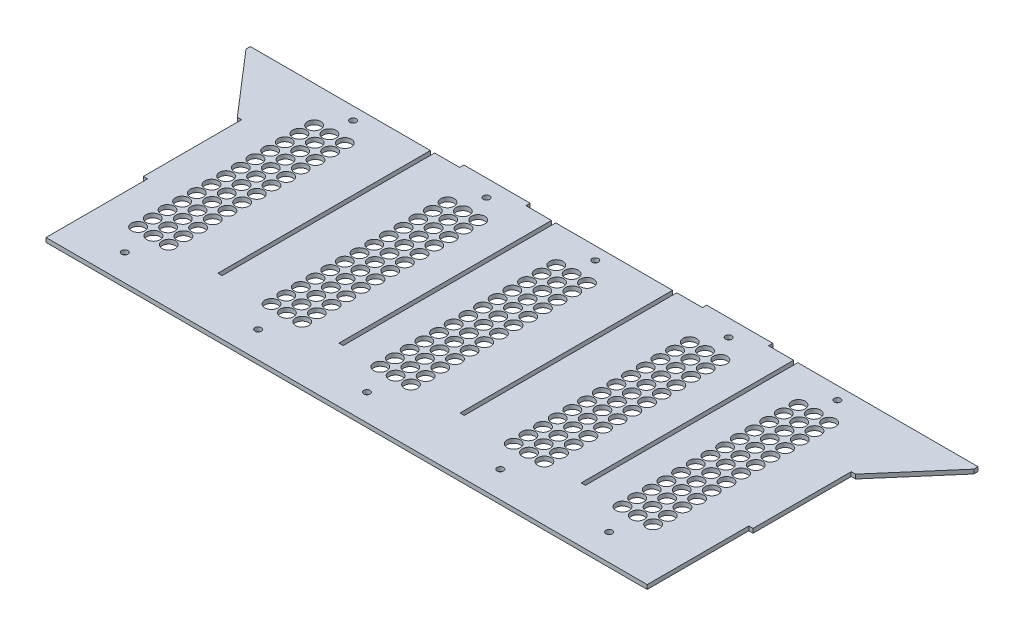
SolidWorks part; units mm, degrees
material "6061-T6 (SS)"
ref_plane "X-Y Datum" through (0, 0, 0) normal (0, 0, 1) x (1, 0, 0)
ref_plane "X-Z Datum" through (0, 0, 0) normal (0, 1, 0) x (1, 0, 0)
ref_plane "Y-Z Datum" through (0, 0, 0) normal (1, 0, 0) x (0, 0, -1)
sketch "Sketch1" plane through (0, 0, 0) normal (0, 0, 1) x (1, 0, 0)
  line L1 (-228.6115, -1.5875) -> (228.6115, -1.5875)
  line L2 (-228.6115, -1.5875) -> (-228.6115, 1.5875)
  line L3 (-228.6115, 1.5875) -> (228.6115, 1.5875)
  line L4 (228.6115, -1.5875) -> (228.6115, 1.5875)
  line L5 (-228.6115, -1.5875) -> (228.6115, 1.5875) construction
  line L6 (-228.6115, 1.5875) -> (228.6115, -1.5875) construction
  point P0 (0, 0)
  dimension "D1" = 3.175
  dimension "D2" = 457.223
extrude "Boss-Extrude1" add sketch "Sketch1" along normal blind 200.642
sketch "Sketch3" plane through (0, 0, 0) normal (0, 0, -1) x (-1, 0, 0)
  line L0 (-66.1907, -1.5583) -> (-66.1907, -1.5875)
  line L9 (228.6115, -1.5875) -> (-228.6115, -1.5875) construction
  line L11 (-228.6115, 1.5875) -> (228.6115, 1.5875) construction
  line L12 (-228.6115, 1.5875) -> (228.6115, 1.5875) construction
  line L13 (-66.1907, -1.5875) -> (-115.8495, -1.5875)
  line L14 (-66.1907, -1.5875) -> (-66.1907, 1.5875)
  line L15 (-66.1907, 1.5875) -> (-115.8495, 1.5875)
  line L16 (-115.8495, -1.5875) -> (-115.8495, 1.5875)
  line L17 (66.1907, -1.5875) -> (115.8495, -1.5875)
  line L18 (66.1907, -1.5875) -> (66.1907, 1.5875)
  line L19 (66.1907, 1.5875) -> (115.8495, 1.5875)
  line L20 (115.8495, -1.5875) -> (115.8495, 1.5875)
  dimension "D2" = 49.6588
sketch "Sketch4" plane through (0, -1.5875, 0) normal (0, -1, 0) x (1, 0, 0)
  line L0 (-228.6115, 0) -> (-272.8865, 0)
  line L2 (-228.6115, 200.642) -> (-228.6115, 0) construction
  line L3 (-228.6115, 50.8) -> (-228.6115, 0)
  line L4 (-272.8865, 0) -> (-272.8865, 3.175)
  line L6 (-228.6115, 50.8) -> (-231.7865, 50.8)
  line L7 (-272.8865, 3.175) -> (-231.7865, 50.8)
  dimension "D1" = 44.275
  dimension "D2" = 50.8
  dimension "D3" = 3.175
  dimension "D4" = 3.175
extrude "Boss-Extrude3" add sketch "Sketch4" against normal blind 3.175
mirror "Mirror1" about plane through (0, 0, 0) normal (1, 0, 0) of "Boss-Extrude3"
sketch "Sketch5" plane through (0, -1.5875, 0) normal (0, -1, 0) x (1, 0, 0)
  line L1 (-228.6115, 200.642) -> (-225.4365, 200.642)
  line L2 (-228.6115, 200.642) -> (-228.6115, 124.442)
  line L3 (-228.6115, 124.442) -> (-225.4365, 124.442)
  line L4 (-225.4365, 200.642) -> (-225.4365, 124.442)
  dimension "D1" = 3.175
  dimension "D2" = 76.2
extrude "Cut-Extrude2" cut sketch "Sketch5" against normal blind 3.175
mirror "Mirror2" about plane through (0, 0, 0) normal (1, 0, 0) of "Cut-Extrude2"
extrude "Boss-Extrude4" add sketch "Sketch3" along normal blind 3.18
sketch "Sketch6" plane through (0, -1.5875, 0) normal (0, -1, 0) x (1, 0, 0)
  point P0 (-186.2355, 9.525)
  point P1 (-186.2355, 180.775)
hole_wizard "M4 Clearance Hole1" positions "Sketch6" profile "Sketch7" hole size "M4" standard "ANSI Metric" end condition through all
sketch "Sketch7" plane through (-186.2355, -1.5875, 9.525) normal (1, 0, 0) x (0, 0, -1)
  line L0 (0, 0) -> (0, 3.175)
  line L1 (0, 3.175) -> (2.4, 3.175)
  line L2 (2.4, 3.175) -> (2.4, 0)
  line L5 (2.4, 0) -> (0, 0)
  line L11 (0, -6.35) -> (0, 107.95) construction
  dimension "Thru Hole Dia." = 4.8
  dimension "Thru Hole Depth" = 3.175
pattern_linear "LPattern5" count 3 spacing 181.614 along (1, 0, 0) of "M4 Clearance Hole1"
sketch "Sketch8" plane through (0, -1.5875, 0) normal (0, -1, 0) x (1, 0, 0)
  point P0 (-86.1905, 9.525)
  point P1 (-86.1905, 180.775)
hole_wizard "M4 Clearance Hole2" positions "Sketch8" profile "Sketch9" hole size "M4" standard "ANSI Metric" end condition through all
sketch "Sketch9" plane through (-86.1905, -1.5875, 9.525) normal (1, 0, 0) x (0, 0, -1)
  line L0 (0, 0) -> (0, 3.175)
  line L1 (0, 3.175) -> (2.4, 3.175)
  line L2 (2.4, 3.175) -> (2.4, 0)
  line L5 (2.4, 0) -> (0, 0)
  line L11 (0, -6.35) -> (0, 107.95) construction
  dimension "Thru Hole Dia." = 4.8
  dimension "Thru Hole Depth" = 3.175
pattern_linear "LPattern6" count 2 spacing 181.614 along (1, 0, 0) of "M4 Clearance Hole2"
sketch "Sketch10" plane through (0, -1.5875, 0) normal (0, -1, 0) x (1, 0, 0)
  circle A0 centre (-174.7355, 159.2567) radius 5 construction
  circle A1 centre (-186.2355, 159.2567) radius 5 construction
  circle A2 centre (-197.7355, 159.2567) radius 5 construction
  circle A3 centre (-174.7355, 159.2567) radius 5
  circle A4 centre (-186.2355, 159.2567) radius 5
  circle A5 centre (-197.7355, 159.2567) radius 5
  circle A6 centre (-74.6905, 159.2567) radius 5 construction
  circle A7 centre (-86.1905, 159.2567) radius 5 construction
  circle A8 centre (-97.6905, 159.2567) radius 5 construction
  circle A9 centre (-74.6905, 159.2567) radius 5
  circle A10 centre (-86.1905, 159.2567) radius 5
  circle A11 centre (-97.6905, 159.2567) radius 5
extrude "Cut-Extrude3" cut sketch "Sketch10" against normal through all contours A5 | A4 | A3
pattern_linear "LPattern1" count 13 spacing 11 along (0, 0, -1) of "Cut-Extrude3"
pattern_linear "LPattern2" count 3 spacing 181.614 along (1, 0, 0) of "Cut-Extrude3", "LPattern1"
sketch "Sketch11" plane through (0, -1.5875, 0) normal (0, -1, 0) x (1, 0, 0)
  circle A1 centre (-74.6905, 159.2567) radius 5
  circle A2 centre (-74.6905, 159.2567) radius 5
  circle A3 centre (-197.7355, 159.2567) radius 5
  circle A4 centre (-197.7355, 159.2567) radius 5
  circle A5 centre (-186.2355, 159.2567) radius 5
  circle A6 centre (-186.2355, 159.2567) radius 5
  circle A7 centre (-174.7355, 159.2567) radius 5
  circle A8 centre (-174.7355, 159.2567) radius 5
  circle A9 centre (-97.6905, 159.2567) radius 5
  circle A10 centre (-97.6905, 159.2567) radius 5
  circle A11 centre (-86.1905, 159.2567) radius 5
  circle A12 centre (-86.1905, 159.2567) radius 5
  dimension "D1" = 0
  dimension "D2" = 0
  dimension "D3" = 0
  dimension "D4" = 0
  dimension "D5" = 0
  dimension "D6" = 0
extrude "Cut-Extrude4" cut sketch "Sketch11" against normal through all contours A10 | A12 | A2
pattern_linear "LPattern3" count 13 spacing 11 along (0, 0, -1) of "Cut-Extrude4"
pattern_linear "LPattern4" count 2 spacing 181.614 along (1, 0, 0) of "LPattern3", "Cut-Extrude4"
sketch "Sketch12" plane through (0, -1.5875, 0) normal (0, -1, 0) x (1, 0, 0)
  line L0 (-134.6255, 159.3868) -> (-134.6255, 0) construction
  line L1 (-137.8005, 159.3868) -> (-137.8005, 0) construction
  line L2 (-137.8005, 159.3868) -> (-134.6255, 159.3868) construction
  line L3 (-134.6255, 159.3868) -> (-134.6255, 0)
  line L4 (-137.8005, 159.3868) -> (-137.8005, 0)
  line L5 (-137.8005, 159.3868) -> (-134.6255, 159.3868)
  line L6 (-272.8865, 0) -> (-115.8495, 0) construction
  line L7 (-272.8865, 0) -> (-115.8495, 0)
  line L8 (-43.8185, 159.3868) -> (-43.8185, 0) construction
  line L9 (-46.9935, 159.3868) -> (-46.9935, 0) construction
  line L10 (-46.9935, 159.3868) -> (-43.8185, 159.3868) construction
  line L11 (-43.8185, 159.3868) -> (-43.8185, 0)
  line L12 (-46.9935, 159.3868) -> (-46.9935, 0)
  line L13 (-46.9935, 159.3868) -> (-43.8185, 159.3868)
  line L14 (43.8135, 159.3868) -> (43.8135, 0) construction
  line L15 (46.9885, 159.3868) -> (46.9885, 0) construction
  line L16 (43.8135, 159.3868) -> (43.8135, 0)
  line L17 (46.9885, 159.3868) -> (46.9885, 0)
  line L18 (43.8135, 159.3868) -> (46.9885, 159.3868) construction
  line L19 (43.8135, 159.3868) -> (46.9885, 159.3868)
  line L20 (137.7955, 159.3868) -> (137.7955, 0) construction
  line L21 (134.6205, 159.3868) -> (134.6205, 0) construction
  line L22 (137.7955, 159.3868) -> (137.7955, 0)
  line L23 (134.6205, 159.3868) -> (134.6205, 0)
  line L24 (134.6205, 159.3868) -> (137.7955, 159.3868) construction
  line L25 (134.6205, 159.3868) -> (137.7955, 159.3868)
  line L26 (-66.1907, 0) -> (66.1907, 0) construction
  line L27 (-66.1907, 0) -> (66.1907, 0)
  line L28 (115.8495, 0) -> (272.8865, 0) construction
  line L29 (115.8495, 0) -> (272.8865, 0)
extrude "Cut-Extrude5" cut sketch "Sketch12" against normal through all contours L4 L7 L3 L5 | L12 L27 L11 L13 | L16 L27 L17 L19 | L23 L29 L22 L25
